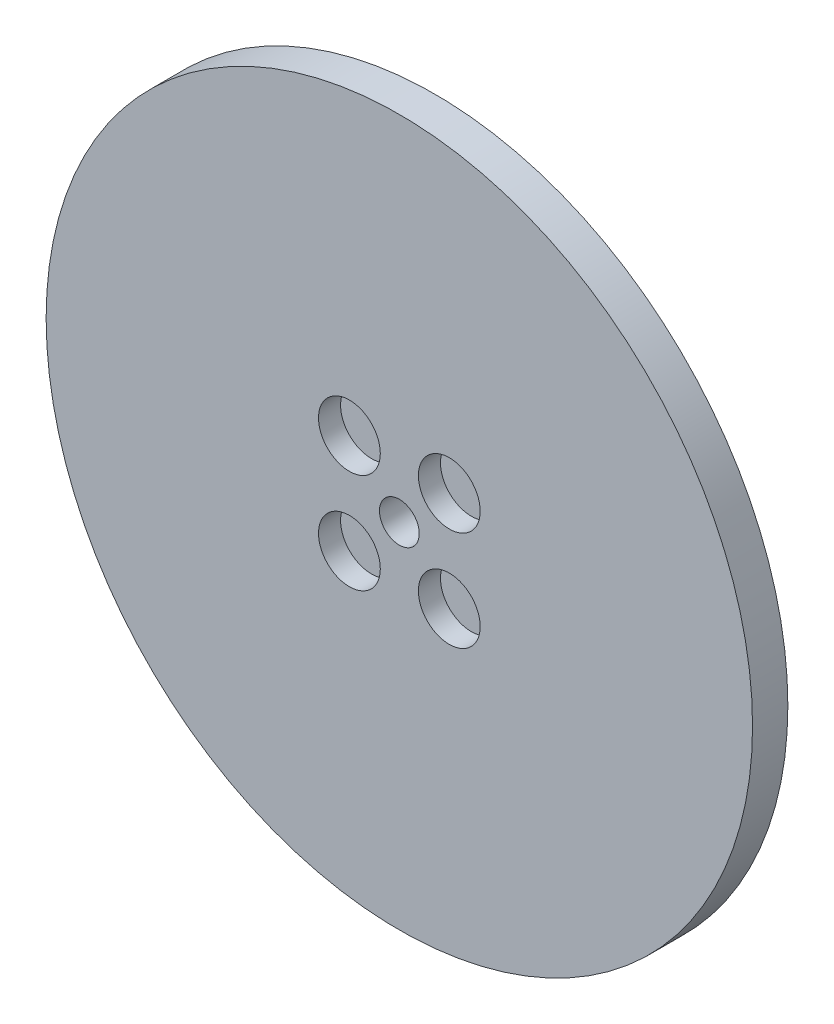
SolidWorks part; units mm, degrees
ref_plane "Front Plane" through (0, 0, 0) normal (0, 0, 1) x (1, 0, 0)
ref_plane "Top Plane" through (0, 0, 0) normal (0, 1, 0) x (1, 0, 0)
ref_plane "Right Plane" through (0, 0, 0) normal (1, 0, 0) x (0, 0, -1)
sketch "Sketch1" plane through (0, 0, 0) normal (0, 0, 1) x (1, 0, 0)
  circle A0 centre (0, 0) radius 12.5
  circle A1 centre (0, 0) radius 30
  dimension "D1" = 25
  dimension "D2" = 60
extrude "Boss-Extrude1" add sketch "Sketch1" along normal blind 4
sketch "Sketch2" plane through (0, 0, 4) normal (0, 0, 1) x (1, 0, 0)
  line L1 (-5.656, 5.6577) -> (5.656, 5.6577) construction
  line L2 (-5.656, 5.6577) -> (-5.656, -5.6577) construction
  line L3 (-5.656, -5.6577) -> (5.656, -5.6577) construction
  line L4 (5.656, 5.6577) -> (5.656, -5.6577) construction
  circle A0 centre (0, 0) radius 2.25
  circle A1 centre (-5.656, 5.6577) radius 1.5
  circle A2 centre (-5.656, -5.6577) radius 1.5
  circle A3 centre (5.656, -5.6577) radius 1.5
  circle A4 centre (5.656, 5.6577) radius 1.5
  circle A5 centre (0, 0) radius 40
  point P15 (0, -5.6577)
  point P16 (-5.656, 0)
  dimension "D1" = 4.5
  dimension "D4" = 3
  dimension "D5" = 80
  dimension "D2" = 16
  dimension "D3" = 11.3154
extrude "Boss-Extrude2" add sketch "Sketch2" along normal blind 4
sketch "Sketch3" plane through (0, 0, 8) normal (0, 0, 1) x (1, 0, 0)
  circle A0 centre (-5.656, 5.6577) radius 3.5
  circle A1 centre (5.656, 5.6577) radius 3.5
  circle A2 centre (5.656, -5.6577) radius 3.5
  circle A3 centre (-5.656, -5.6577) radius 3.5
  dimension "D1" = 7
extrude "Cut-Extrude1" cut sketch "Sketch3" against normal blind 2.5
sketch "Sketch4" plane through (0, 0, 0) normal (0, 0, -1) x (-1, 0, 0)
  circle A0 centre (-20, 0) radius 5.15
  circle A1 centre (0, -20) radius 5.15
  circle A2 centre (0, 0) radius 20 construction
  circle A3 centre (0, 0) radius 20 construction
  circle A4 centre (20, 0) radius 5.15
  circle A5 centre (0, 0) radius 20 construction
  circle A6 centre (0, 20) radius 5.15
  circle A7 centre (0, 0) radius 20 construction
  point P17 (0, 0)
  dimension "D1" = 10.3
  dimension "D2" = 40
  dimension "D3" = 4
extrude "Cut-Extrude2" cut sketch "Sketch4" against normal blind 4
sketch "Sketch5" plane through (0, 0, 5.5) normal (0, 0, 1) x (1, 0, 0)
  circle A0 centre (-5.656, 5.6577) radius 3.5
  circle A1 centre (5.656, 5.6577) radius 3.5
  circle A2 centre (-5.656, -5.6577) radius 3.5
  circle A3 centre (5.656, -5.6577) radius 3.5
extrude "Boss-Extrude3" add sketch "Sketch5" against normal blind 0.2
